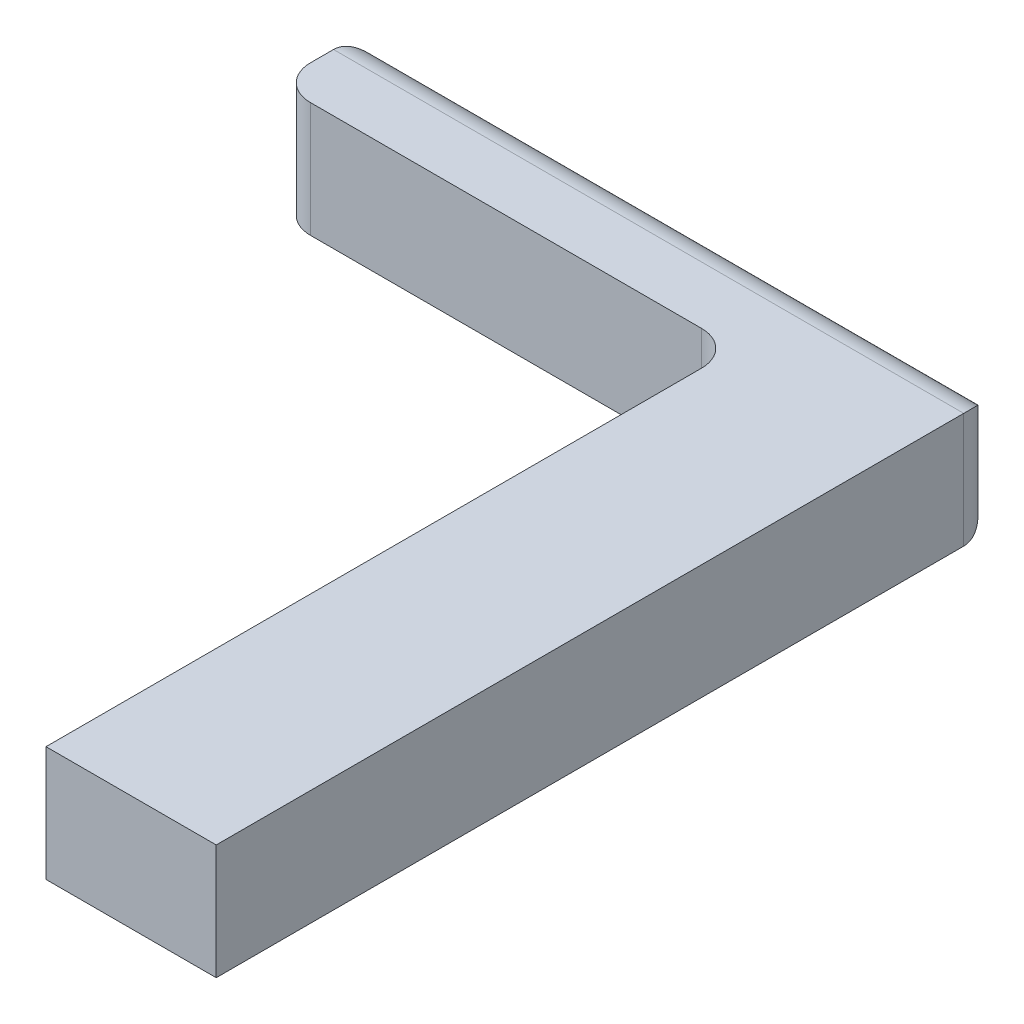
SolidWorks part; units mm, degrees
ref_plane "Front Plane" through (0, 0, 0) normal (0, 0, 1) x (1, 0, 0)
ref_plane "Top Plane" through (0, 0, 0) normal (0, 1, 0) x (1, 0, 0)
ref_plane "Right Plane" through (0, 0, 0) normal (1, 0, 0) x (0, 0, -1)
sketch "Sketch1" plane through (0, 0, 0) normal (0, 1, 0) x (1, 0, 0)
  line L1 (7.4, 34) -> (-7.4, 34)
  line L2 (7.4, 34) -> (7.4, -34)
  line L3 (7.4, -34) -> (-7.4, -34)
  line L4 (-7.4, 34) -> (-7.4, -34)
  line L5 (7.4, 34) -> (-7.4, -34) construction
  line L6 (7.4, -34) -> (-7.4, 34) construction
  point P0 (0, 0)
  dimension "D1" = 68
  dimension "D2" = 14.8
extrude "Boss-Extrude1" add sketch "Sketch1" along normal blind 10
sketch "Sketch2" plane through (-7.4, 0, 0) normal (-1, 0, 0) x (0, 0, 1)
  line L0 (-34, 0) -> (34, 0) construction
  line L1 (-34, 10) -> (-26, 10)
  line L2 (-34, 10) -> (-34, 0)
  line L3 (-34, 0) -> (-26, 0)
  line L4 (-26, 10) -> (-26, 0)
  dimension "D1" = 8
extrude "Boss-Extrude2" add sketch "Sketch2" along normal blind 40
fillet "Fillet2" radius 3 6 edges at (-20, 10, -34) (-20, 0, -34) (-47.4, 5, -34) (-47.4, 5, -26) (7.4, 5, -34) (-7.4, 5, -26)
